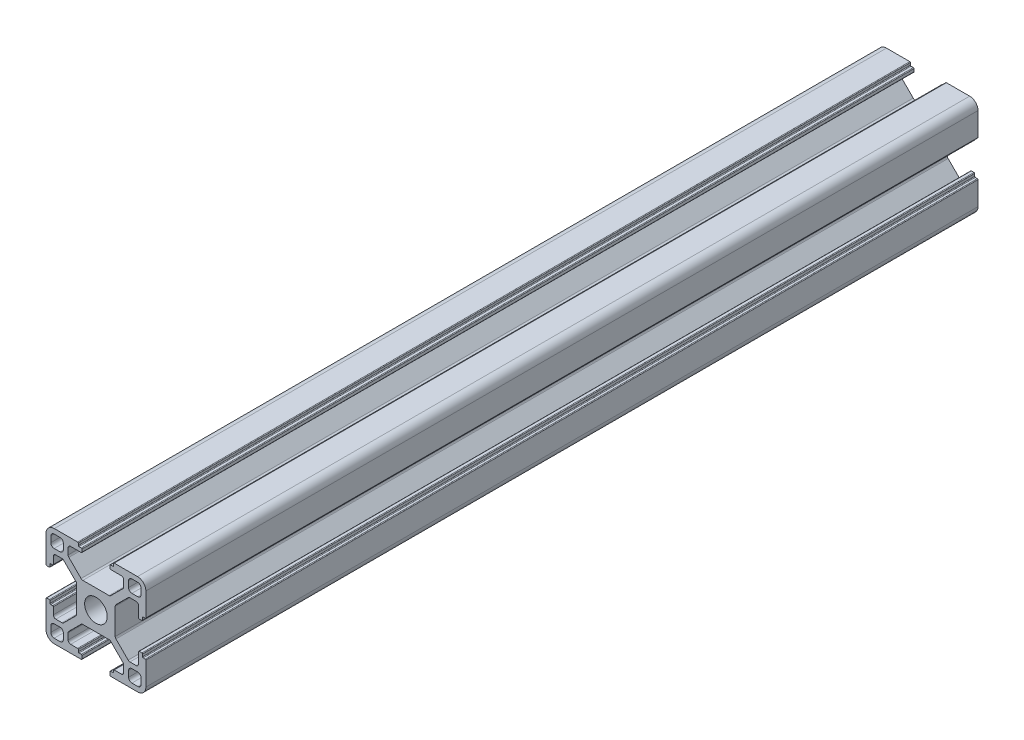
SolidWorks part; units mm, degrees
material "6063-T5"
ref_plane "Front Plane" through (0, 0, 0) normal (0, 0, 1) x (1, 0, 0)
ref_plane "Top Plane" through (0, 0, 0) normal (0, 1, 0) x (1, 0, 0)
ref_plane "Right Plane" through (0, 0, 0) normal (1, 0, 0) x (0, 0, -1)
sketch "Sketch1" plane through (0, 0, 0) normal (0, 0, 1) x (1, 0, 0)
  line L0 (0, 2.5) -> (0, 10.6)
  line L1 (2.5, 30) -> (9.5, 30)
  line L2 (30, 27.5) -> (30, 20.5)
  line L3 (27.5, 0) -> (19.4, 0)
  line L4 (19.464, 9.1128) -> (23.1303, 5.4465)
  line L5 (21.0197, 10.536) -> (24.686, 6.8697)
  line L6 (10.536, 21.0197) -> (6.8697, 24.686)
  line L7 (8.9803, 19.464) -> (5.314, 23.1303)
  line L8 (11.0663, 20.8) -> (18.9337, 20.8)
  line L9 (20.8, 18.9337) -> (20.8, 11.0663)
  line L10 (18.9337, 9.3324) -> (11.0663, 9.3324)
  line L11 (9.2, 11.0663) -> (9.2, 18.9337)
  line L12 (0, 19.4) -> (0, 27.5)
  line L13 (30, 9.5) -> (30, 2.5)
  line L14 (19.4, 27.8) -> (22.6, 27.8)
  line L15 (10.6, 27.8) -> (7.4, 27.8)
  line L16 (10.6, 0) -> (2.5, 0)
  line L17 (2.2, 20.5) -> (2.2, 22.6)
  line L18 (2.2, 9.5) -> (2.2, 7.4)
  line L19 (9.5, 2.3324) -> (7.4, 2.3324)
  line L20 (19.464, 21.0197) -> (23.1303, 24.686)
  line L21 (21.0197, 19.464) -> (24.686, 23.1303)
  line L22 (8.9803, 10.536) -> (5.314, 6.8697)
  line L23 (10.536, 9.1128) -> (6.8697, 5.4465)
  line L24 (10.8, 28.8) -> (10.8, 28)
  line L25 (19.2, 28.8) -> (19.2, 28)
  line L26 (0.2, 19.2) -> (1, 19.2)
  line L27 (0.2, 10.8) -> (1, 10.8)
  line L28 (28.8, 19.2) -> (28, 19.2)
  line L29 (28.8, 10.8) -> (28, 10.8)
  line L30 (10.8, 0.2) -> (10.8, 1.1324)
  line L31 (19.2, 0.2) -> (19.2, 1.1324)
  line L32 (20.5, 30) -> (27.5, 30)
  line L33 (27.8, 19.4) -> (27.8, 22.6)
  line L34 (27.8, 10.6) -> (27.8, 7.4)
  line L35 (20.5, 2.2) -> (22.6, 2.2)
  line L36 (6.65, 27.05) -> (6.65, 25.2163)
  line L37 (23.35, 27.05) -> (23.35, 25.2163)
  line L38 (2.95, 23.35) -> (4.7837, 23.35)
  line L39 (27.05, 23.35) -> (25.2163, 23.35)
  line L40 (2.95, 6.65) -> (4.7837, 6.65)
  line L41 (6.65, 3.0824) -> (6.65, 4.9161)
  line L42 (23.35, 2.95) -> (23.35, 4.9161)
  line L43 (27.05, 6.65) -> (25.2163, 6.65)
  line L44 (29, 10.6) -> (29, 9.9)
  line L45 (29.8, 20.3) -> (29.2, 20.3)
  line L46 (29, 20.1) -> (29, 19.4)
  line L47 (29.2, 9.7) -> (29.8, 9.7)
  line L48 (19.4, 29) -> (20.1, 29)
  line L49 (9.7, 29.8) -> (9.7, 29.2)
  line L50 (9.9, 29) -> (10.6, 29)
  line L51 (20.3, 29.2) -> (20.3, 29.8)
  line L52 (9.7, 2.1324) -> (9.7, 1.5324)
  line L53 (9.9, 1.3324) -> (10.6, 1.3324)
  line L54 (19.4, 1.3324) -> (20.1, 1.3324)
  line L55 (20.3, 1.5324) -> (20.3, 2)
  line L56 (2, 20.3) -> (1.4, 20.3)
  line L57 (1.2, 20.1) -> (1.2, 19.4)
  line L58 (1.2, 10.6) -> (1.2, 9.9)
  line L59 (1.4, 9.7) -> (2, 9.7)
  line L60 (27.55, 1.45) -> (25.8, 1.45)
  line L61 (24.8, 2.45) -> (24.8, 4.2)
  line L62 (25.8, 5.2) -> (27.55, 5.2)
  line L63 (28.55, 4.2) -> (28.55, 2.45)
  line L64 (24.8, 25.8) -> (24.8, 27.55)
  line L65 (25.8, 28.55) -> (27.55, 28.55)
  line L66 (28.55, 27.55) -> (28.55, 25.8)
  line L67 (27.55, 24.8) -> (25.8, 24.8)
  line L68 (2.45, 28.55) -> (4.2, 28.55)
  line L69 (5.2, 27.55) -> (5.2, 25.8)
  line L70 (1.45, 2.45) -> (1.45, 4.2)
  line L71 (2.45, 5.2) -> (4.2, 5.2)
  line L72 (5.2, 4.2) -> (5.2, 2.45)
  line L73 (4.2, 1.45) -> (2.45, 1.45)
  line L74 (4.2, 24.8) -> (2.45, 24.8)
  line L75 (1.45, 25.8) -> (1.45, 27.55)
  circle A0 centre (15, 15) radius 3.4
  arc A1 (25.8, 1.45) -> (24.8, 2.45) centre (25.8, 2.45) cw
  arc A2 (27.55, 1.45) -> (28.55, 2.45) centre (27.55, 2.45) ccw
  arc A3 (27.55, 5.2) -> (28.55, 4.2) centre (27.55, 4.2) cw
  arc A4 (24.8, 4.2) -> (25.8, 5.2) centre (25.8, 4.2) cw
  arc A5 (1.45, 2.45) -> (2.45, 1.45) centre (2.45, 2.45) ccw
  arc A6 (5.2, 2.45) -> (4.2, 1.45) centre (4.2, 2.45) cw
  arc A7 (4.2, 5.2) -> (5.2, 4.2) centre (4.2, 4.2) cw
  arc A8 (1.45, 4.2) -> (2.45, 5.2) centre (2.45, 4.2) cw
  arc A9 (24.8, 25.8) -> (25.8, 24.8) centre (25.8, 25.8) ccw
  arc A10 (28.55, 25.8) -> (27.55, 24.8) centre (27.55, 25.8) cw
  arc A11 (27.55, 28.55) -> (28.55, 27.55) centre (27.55, 27.55) cw
  arc A12 (24.8, 27.55) -> (25.8, 28.55) centre (25.8, 27.55) cw
  arc A13 (4.2, 28.55) -> (5.2, 27.55) centre (4.2, 27.55) cw
  arc A14 (5.2, 25.8) -> (4.2, 24.8) centre (4.2, 25.8) cw
  arc A15 (2.45, 24.8) -> (1.45, 25.8) centre (2.45, 25.8) cw
  arc A16 (2.45, 28.55) -> (1.45, 27.55) centre (2.45, 27.55) ccw
  arc A17 (30, 2.5) -> (27.5, 0) centre (27.5, 2.5) cw
  arc A18 (0, 2.5) -> (2.5, 0) centre (2.5, 2.5) ccw
  arc A19 (27.5, 30) -> (30, 27.5) centre (27.5, 27.5) cw
  arc A20 (0, 27.5) -> (2.5, 30) centre (2.5, 27.5) cw
  arc A21 (0, 10.6) -> (0.2, 10.8) centre (0.2, 10.6) cw
  arc A22 (1.2, 10.6) -> (1, 10.8) centre (1, 10.6) ccw
  arc A23 (2, 9.7) -> (2.2, 9.5) centre (2, 9.5) cw
  arc A24 (9.7, 2.1324) -> (9.5, 2.3324) centre (9.5, 2.1324) ccw
  arc A25 (10.6, 1.3324) -> (10.8, 1.1324) centre (10.6, 1.1324) cw
  arc A26 (10.6, 0) -> (10.8, 0.2) centre (10.6, 0.2) ccw
  arc A27 (19.4, 0) -> (19.2, 0.2) centre (19.4, 0.2) cw
  arc A28 (19.4, 1.3324) -> (19.2, 1.1324) centre (19.4, 1.1324) ccw
  arc A29 (20.3, 2) -> (20.5, 2.2) centre (20.5, 2) cw
  arc A30 (28, 10.8) -> (27.8, 10.6) centre (28, 10.6) ccw
  arc A31 (29, 10.6) -> (28.8, 10.8) centre (28.8, 10.6) ccw
  arc A32 (29.8, 9.7) -> (30, 9.5) centre (29.8, 9.5) cw
  arc A33 (28, 19.2) -> (27.8, 19.4) centre (28, 19.4) cw
  arc A34 (29, 19.4) -> (28.8, 19.2) centre (28.8, 19.4) cw
  arc A35 (30, 20.5) -> (29.8, 20.3) centre (29.8, 20.5) cw
  arc A36 (20.3, 29.8) -> (20.5, 30) centre (20.5, 29.8) cw
  arc A37 (19.4, 29) -> (19.2, 28.8) centre (19.4, 28.8) ccw
  arc A38 (19.2, 28) -> (19.4, 27.8) centre (19.4, 28) ccw
  arc A39 (10.8, 28) -> (10.6, 27.8) centre (10.6, 28) cw
  arc A40 (0, 19.4) -> (0.2, 19.2) centre (0.2, 19.4) ccw
  arc A41 (1.2, 19.4) -> (1, 19.2) centre (1, 19.4) cw
  arc A42 (2, 20.3) -> (2.2, 20.5) centre (2, 20.5) ccw
  arc A43 (10.6, 29) -> (10.8, 28.8) centre (10.6, 28.8) cw
  arc A44 (9.5, 30) -> (9.7, 29.8) centre (9.5, 29.8) cw
  arc A45 (1.4, 20.3) -> (1.2, 20.1) centre (1.4, 20.1) ccw
  arc A46 (20.1, 29) -> (20.3, 29.2) centre (20.1, 29.2) ccw
  arc A47 (9.7, 29.2) -> (9.9, 29) centre (9.9, 29.2) ccw
  arc A48 (29.2, 20.3) -> (29, 20.1) centre (29.2, 20.1) ccw
  arc A49 (29, 9.9) -> (29.2, 9.7) centre (29.2, 9.9) ccw
  arc A50 (20.1, 1.3324) -> (20.3, 1.5324) centre (20.1, 1.5324) ccw
  arc A51 (1.2, 9.9) -> (1.4, 9.7) centre (1.4, 9.9) ccw
  arc A52 (9.7, 1.5324) -> (9.9, 1.3324) centre (9.9, 1.5324) ccw
  arc A53 (23.35, 25.2163) -> (23.1303, 24.686) centre (22.6, 25.2163) cw
  arc A54 (25.2163, 23.35) -> (24.686, 23.1303) centre (25.2163, 22.6) ccw
  arc A55 (20.8, 18.9337) -> (21.0197, 19.464) centre (21.55, 18.9337) cw
  arc A56 (18.9337, 20.8) -> (19.464, 21.0197) centre (18.9337, 21.55) ccw
  arc A57 (6.65, 25.2163) -> (6.8697, 24.686) centre (7.4, 25.2163) ccw
  arc A58 (11.0663, 20.8) -> (10.536, 21.0197) centre (11.0663, 21.55) cw
  arc A59 (4.7837, 23.35) -> (5.314, 23.1303) centre (4.7837, 22.6) cw
  arc A60 (9.2, 18.9337) -> (8.9803, 19.464) centre (8.45, 18.9337) ccw
  arc A61 (4.7837, 6.65) -> (5.314, 6.8697) centre (4.7837, 7.4) ccw
  arc A62 (9.2, 11.0663) -> (8.9803, 10.536) centre (8.45, 11.0663) cw
  arc A63 (6.65, 4.9161) -> (6.8697, 5.4465) centre (7.4, 4.9161) cw
  arc A64 (11.0663, 9.3324) -> (10.536, 9.1128) centre (11.0663, 8.5824) ccw
  arc A65 (18.9337, 9.3324) -> (19.464, 9.1128) centre (18.9337, 8.5824) cw
  arc A66 (20.8, 11.0663) -> (21.0197, 10.536) centre (21.55, 11.0663) ccw
  arc A67 (25.2163, 6.65) -> (24.686, 6.8697) centre (25.2163, 7.4) cw
  arc A68 (23.35, 4.9161) -> (23.1303, 5.4465) centre (22.6, 4.9161) ccw
  arc A69 (7.4, 2.3324) -> (6.65, 3.0824) centre (7.4, 3.0824) cw
  arc A70 (22.6, 2.2) -> (23.35, 2.95) centre (22.6, 2.95) ccw
  arc A71 (27.8, 7.4) -> (27.05, 6.65) centre (27.05, 7.4) cw
  arc A72 (27.8, 22.6) -> (27.05, 23.35) centre (27.05, 22.6) ccw
  arc A73 (22.6, 27.8) -> (23.35, 27.05) centre (22.6, 27.05) cw
  arc A74 (2.2, 7.4) -> (2.95, 6.65) centre (2.95, 7.4) ccw
  arc A75 (2.2, 22.6) -> (2.95, 23.35) centre (2.95, 22.6) cw
  arc A76 (7.4, 27.8) -> (6.65, 27.05) centre (7.4, 27.05) ccw
  point P115 (0, 0)
extrude "Boss-Extrude1" add sketch "Sketch1" along normal blind 250
